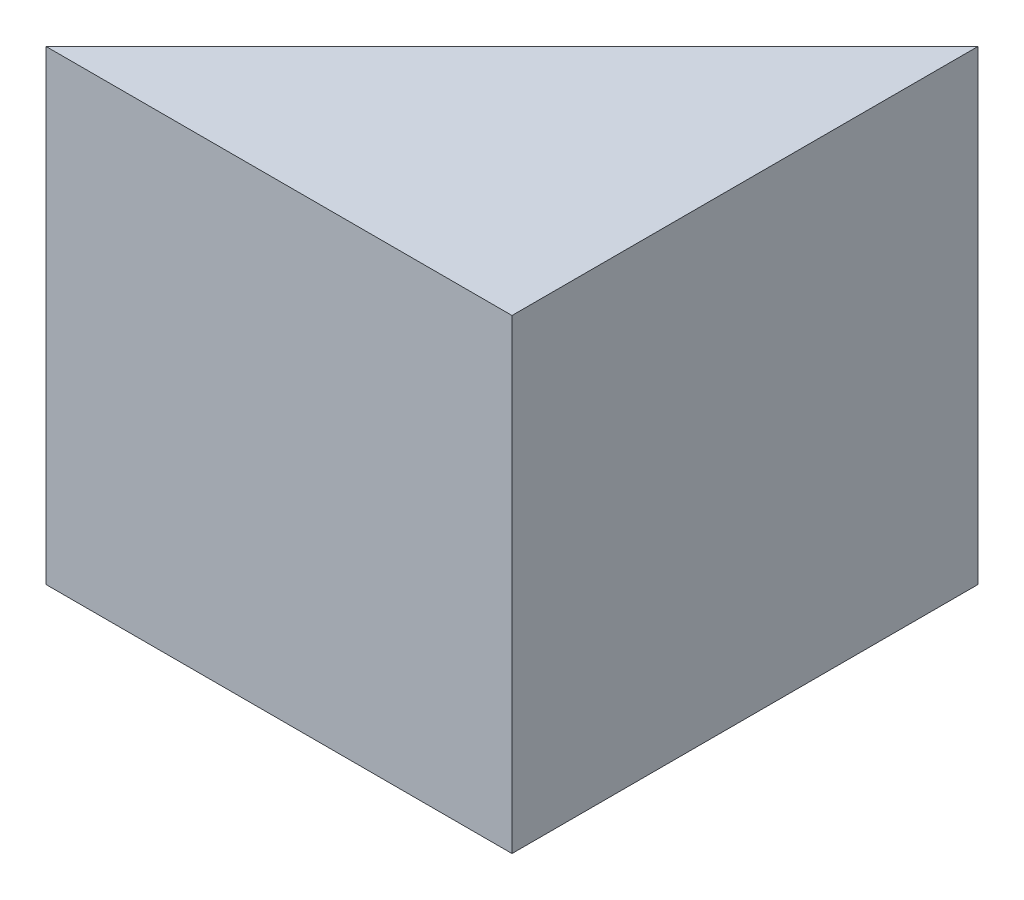
SolidWorks part; units mm, degrees
ref_plane "Front Plane" through (0, 0, 0) normal (0, 0, 1) x (1, 0, 0)
ref_plane "Top Plane" through (0, 0, 0) normal (0, 1, 0) x (1, 0, 0)
ref_plane "Right Plane" through (0, 0, 0) normal (1, 0, 0) x (0, 0, -1)
sketch "Sketch1" plane through (0, 0, 0) normal (0, 1, 0) x (1, 0, 0)
  line L1 (0, 0) -> (1, 0)
  line L2 (0, 0) -> (0, 1)
  line L3 (0, 1) -> (1, 1)
  line L4 (1, 0) -> (1, 1)
  dimension "D1" = 1
  dimension "D2" = 1
extrude "Boss-Extrude1" add sketch "Sketch1" along normal blind 1
sketch "Sketch3" plane through (0, 1, 0) normal (0, 1, 0) x (1, 0, 0)
  line L0 (0, 0) -> (1, 1)
extrude "Cut-Extrude1" cut sketch "Sketch3" against normal blind 0.5 and the other way through all
